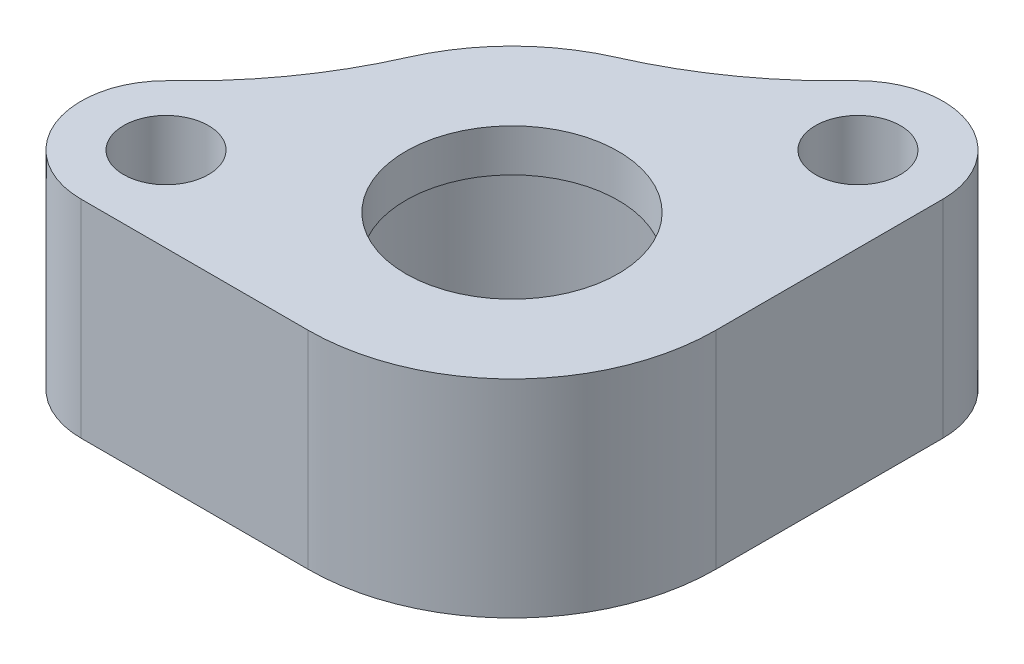
SolidWorks part; units mm, degrees
ref_plane "Front Plane" through (0, 0, 0) normal (0, 0, 1) x (1, 0, 0)
ref_plane "Top Plane" through (0, 0, 0) normal (0, 1, 0) x (1, 0, 0)
ref_plane "Right Plane" through (0, 0, 0) normal (1, 0, 0) x (0, 0, -1)
sketch "Sketch1" plane through (0, 0, 0) normal (0, 1, 0) x (1, 0, 0)
  line L0 (0, -9.6) -> (-10.6912, -9.6)
  line L1 (-13.5196, -2.7716) -> (2.7716, 13.5196)
  line L2 (0, 0) -> (-5.374, 5.374) construction
  line L3 (9.6, 0) -> (9.6, 10.6912)
  circle A0 centre (0, 0) radius 7.6
  circle A1 centre (0, 0) radius 9.6
  arc A2 (-10.6912, -9.6) -> (-13.5196, -2.7716) centre (-10.6912, -5.6) cw
  arc A3 (9.6, 10.6912) -> (2.7716, 13.5196) centre (5.6, 10.6912) ccw
  circle A4 centre (-10.6912, -5.6) radius 2
  circle A5 centre (5.6, 10.6912) radius 2
  dimension "D1" = 15.2
  dimension "D2" = 4
  dimension "D3" = 2
  dimension "D5" = 4
  dimension "D4" = 45
extrude "Boss-Extrude1" add sketch "Sketch1" along normal blind 7.75 contours A2 L0 A1 L1 A4 | L1 A1 | A1 L1 A0 | L3 A3 L1 A1 A5
sketch "Sketch2" plane through (0, 7.75, 0) normal (0, 1, 0) x (1, 0, 0)
  line L4 (9.6, 0) -> (9.6, 10.6912)
  line L5 (2.7716, 13.5196) -> (-1.2267, 9.5213)
  line L6 (-9.5213, 1.2267) -> (-13.5196, -2.7716)
  line L7 (-10.6912, -9.6) -> (0, -9.6)
  line L8 (9.6, 0) -> (9.6, 10.6912)
  line L9 (2.7716, 13.5196) -> (-1.2267, 9.5213)
  line L10 (-9.5213, 1.2267) -> (-13.5196, -2.7716)
  line L11 (-10.6912, -9.6) -> (0, -9.6)
  circle A2 centre (-10.6912, -5.6) radius 2 construction
  circle A3 centre (-10.6912, -5.6) radius 2
  arc A4 (0, -9.6) -> (9.6, 0) centre (0, 0) ccw
  arc A5 (9.6, 10.6912) -> (2.7716, 13.5196) centre (5.6, 10.6912) ccw
  arc A6 (-1.2267, 9.5213) -> (-9.5213, 1.2267) centre (0, 0) ccw
  arc A7 (-13.5196, -2.7716) -> (-10.6912, -9.6) centre (-10.6912, -5.6) ccw
  arc A8 (0, -9.6) -> (9.6, 0) centre (0, 0) ccw
  arc A9 (9.6, 10.6912) -> (2.7716, 13.5196) centre (5.6, 10.6912) ccw
  arc A10 (-1.2267, 9.5213) -> (-9.5213, 1.2267) centre (0, 0) ccw
  arc A11 (-13.5196, -2.7716) -> (-10.6912, -9.6) centre (-10.6912, -5.6) ccw
  circle A12 centre (5.6, 10.6912) radius 2 construction
  circle A13 centre (5.6, 10.6912) radius 2
  circle A14 centre (0, 0) radius 5
  dimension "D2" = 10
  dimension "D1" = 0
extrude "Boss-Extrude2" add sketch "Sketch2" along normal blind 2
fillet "Fillet1" radius 20 2 edges at (-9.5213, 4.875, -1.2267) (-1.2267, 4.875, -9.5213)
